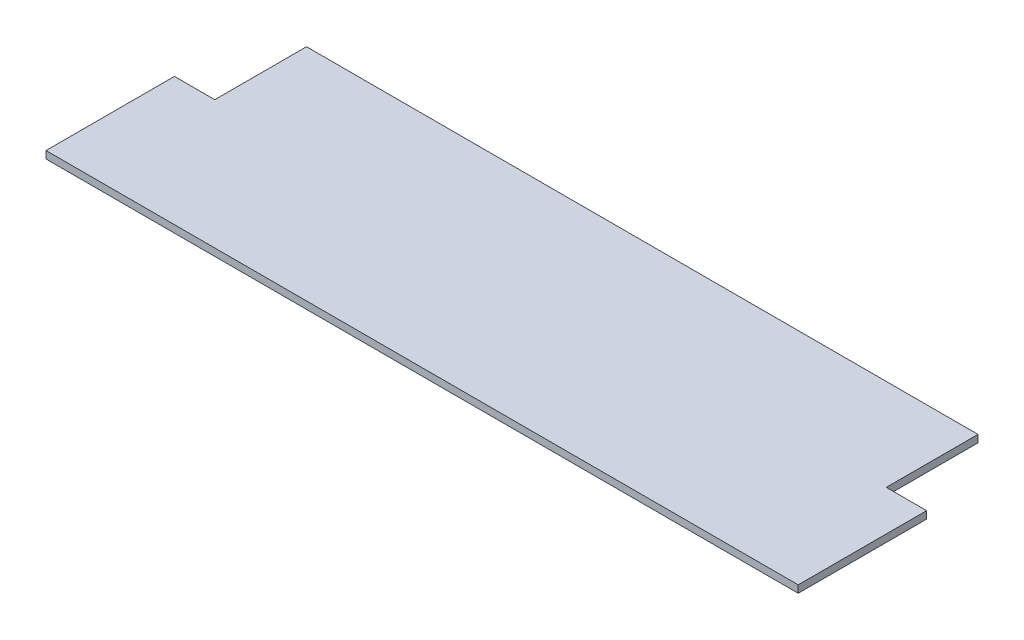
SolidWorks part; units mm, degrees
ref_plane "Front Plane" through (0, 0, 0) normal (0, 0, 1) x (1, 0, 0)
ref_plane "Top Plane" through (0, 0, 0) normal (0, 1, 0) x (1, 0, 0)
ref_plane "Right Plane" through (0, 0, 0) normal (1, 0, 0) x (0, 0, -1)
sketch "Sketch1" plane through (0, 0, 0) normal (0, 1, 0) x (1, 0, 0)
  line L1 (-205, 60) -> (205, 60)
  line L2 (-205, 60) -> (-205, -60)
  line L3 (-205, -60) -> (205, -60)
  line L4 (205, 60) -> (205, -60)
  line L5 (-205, 60) -> (205, -60) construction
  line L6 (-205, -60) -> (205, 60) construction
  point P0 (0, 0)
  dimension "D1" = 120
  dimension "D2" = 410
extrude "Boss-Extrude1" add sketch "Sketch1" along normal blind 4
sketch "Sketch2" plane through (0, 4, 0) normal (0, 1, 0) x (1, 0, 0)
  line L1 (183, 10) -> (233.1702, 10)
  line L2 (183, 10) -> (183, 80.735)
  line L3 (183, 80.735) -> (233.1702, 80.735)
  line L4 (233.1702, 10) -> (233.1702, 80.735)
  line L6 (0, -2.2) -> (0, 2.2) construction
  line L7 (-183, 10) -> (-183, 80.735)
  line L8 (-183, 10) -> (-233.1702, 10)
  line L9 (-233.1702, 10) -> (-233.1702, 80.735)
  line L10 (-183, 80.735) -> (-233.1702, 80.735)
extrude "Cut-Extrude1" cut sketch "Sketch2" against normal up to next
